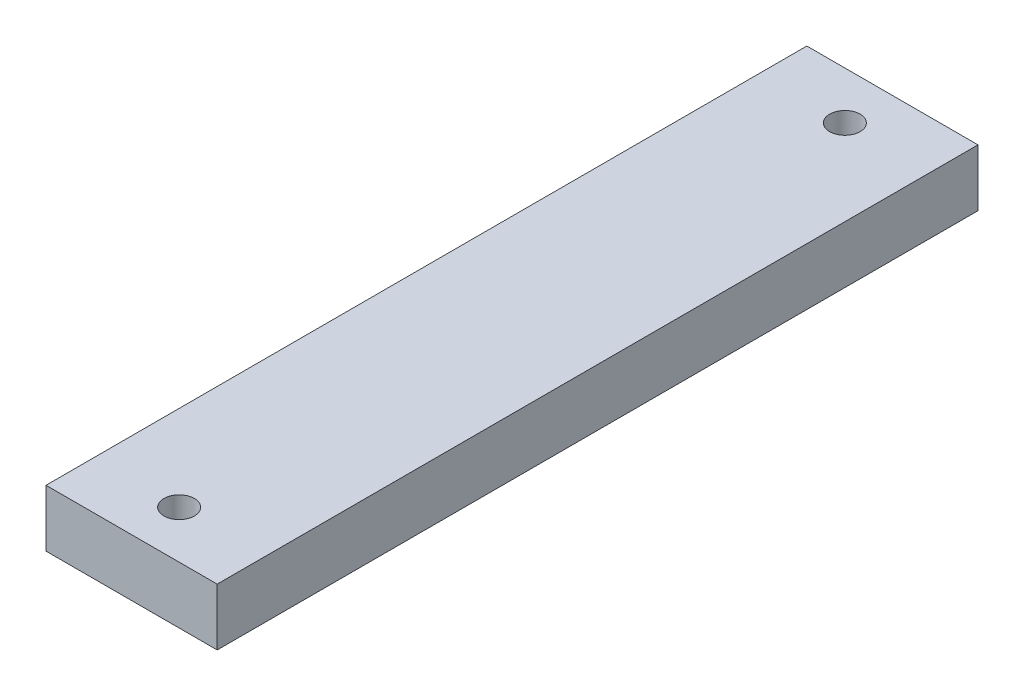
SolidWorks part; units mm, degrees
material "Oak"
ref_plane "Front Plane" through (0, 0, 0) normal (0, 0, 1) x (1, 0, 0)
ref_plane "Top Plane" through (0, 0, 0) normal (0, 1, 0) x (1, 0, 0)
ref_plane "Right Plane" through (0, 0, 0) normal (1, 0, 0) x (0, 0, -1)
sketch "Sketch1" plane through (0, 0, 0) normal (0, 1, 0) x (1, 0, 0)
  line L0 (-55, 0) -> (55, 0) construction
  line L1 (-9, -40) -> (9, -40)
  line L2 (-9, -40) -> (-9, 40)
  line L3 (-9, 40) -> (9, 40)
  line L4 (9, -40) -> (9, 40)
  line L5 (-9, -40) -> (9, 40) construction
  line L6 (-9, 40) -> (9, -40) construction
  circle A0 centre (0, -35) radius 1.6
  circle A1 centre (0, 35) radius 1.6
  point P0 (0, 0)
  point P8 (0, 0)
  dimension "D3" = 3.2
  dimension "D4" = 5
  dimension "D1" = 18
  dimension "D2" = 80
extrude "Boss-Extrude1" add sketch "Sketch1" along normal blind 6
